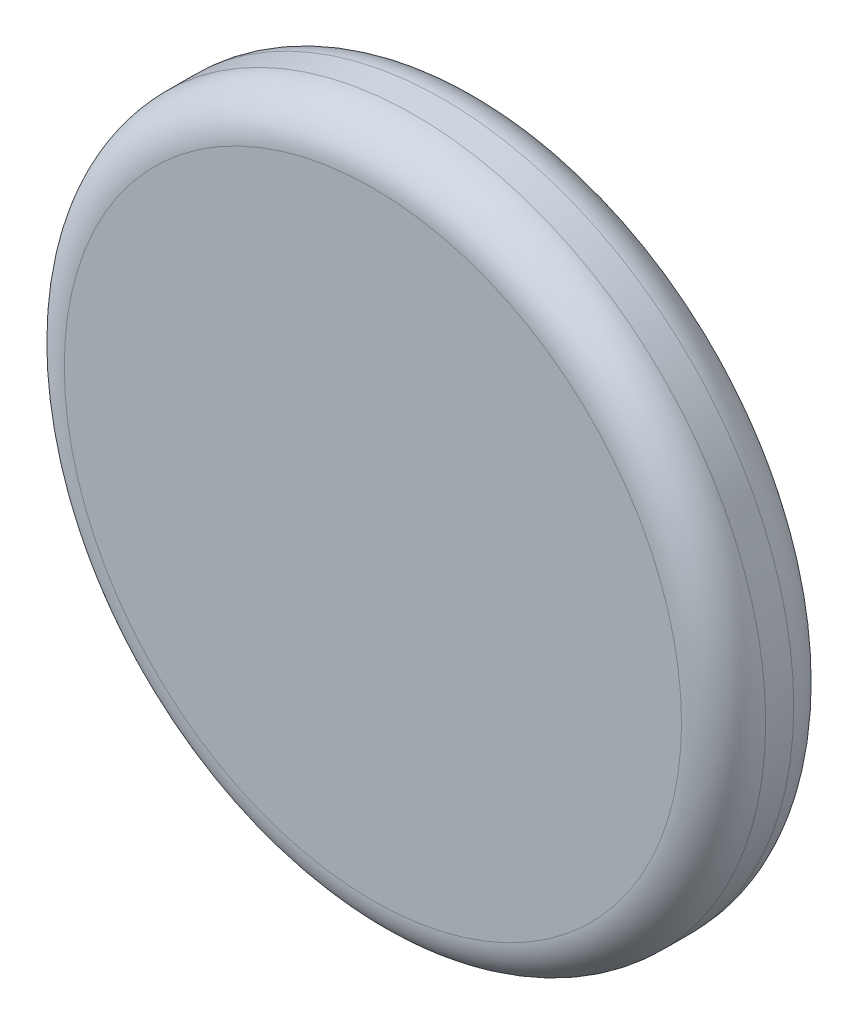
SolidWorks part; units mm, degrees
ref_plane "Front Plane" through (0, 0, 0) normal (0, 0, 1) x (1, 0, 0)
ref_plane "Top Plane" through (0, 0, 0) normal (0, 1, 0) x (1, 0, 0)
ref_plane "Right Plane" through (0, 0, 0) normal (1, 0, 0) x (0, 0, -1)
sketch "Sketch1" plane through (0, 0, 0) normal (0, 0, 1) x (1, 0, 0)
  circle A0 centre (0, 0) radius 12.5
  dimension "D1" = 25
extrude "Boss-Extrude1" add sketch "Sketch1" along normal blind 4
fillet "Fillet2" radius 1.5 2 edges at (12.5, 0, 0) (12.5, 0, 4)
